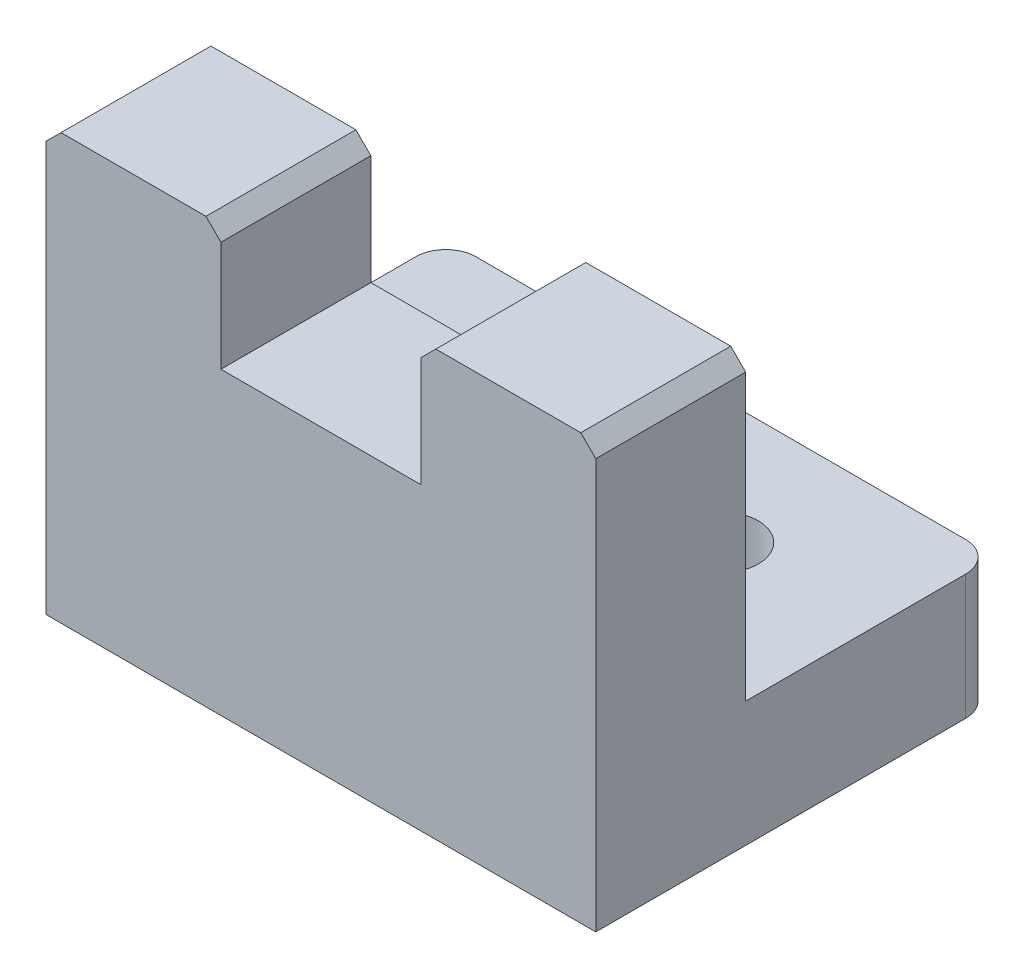
SolidWorks part; units mm, degrees
ref_plane "Front Plane" through (0, 0, 0) normal (0, 0, 1) x (1, 0, 0)
ref_plane "Top Plane" through (0, 0, 0) normal (0, 1, 0) x (1, 0, 0)
ref_plane "Right Plane" through (0, 0, 0) normal (1, 0, 0) x (0, 0, -1)
sketch "Sketch1" plane through (0, 0, 0) normal (0, 1, 0) x (1, 0, 0)
  line L1 (-55, 40) -> (55, 40)
  line L2 (-55, 40) -> (-55, -40)
  line L3 (-55, -40) -> (55, -40)
  line L4 (55, 40) -> (55, -40)
  dimension "D1" = 110
  dimension "D2" = 80
  dimension "D3" = 40
  dimension "D4" = 55
extrude "Boss-Extrude1" add sketch "Sketch1" along normal mid plane 25
sketch "Sketch2" plane through (0, 12.5, 0) normal (0, 1, 0) x (1, 0, 0)
  line L0 (55, -40) -> (55, 40) construction
  line L1 (-55, -40) -> (55, -40)
  line L2 (-55, -40) -> (-55, -10)
  line L3 (-55, -10) -> (55, -10)
  line L4 (55, -40) -> (55, -10)
  dimension "D1" = 30
extrude "Boss-Extrude2" add sketch "Sketch2" along normal blind 60
sketch "Sketch3" plane through (0, 0, 10) normal (0, 0, -1) x (-1, 0, 0)
  line L0 (-55, 72.5) -> (55, 72.5) construction
  line L1 (-20, 72.5) -> (20, 72.5)
  line L2 (-20, 72.5) -> (-20, 47.5)
  line L3 (-20, 47.5) -> (20, 47.5)
  line L4 (20, 72.5) -> (20, 47.5)
  line L5 (-55, 72.5) -> (-55, 12.5) construction
  dimension "D1" = 40
  dimension "D2" = 35
  dimension "D3" = 25
extrude "Cut-Extrude1" cut sketch "Sketch3" against normal through all
chamfer "Chamfer1" distance 3 distance2 3 4 edges at (55, 72.5, 25) (20, 72.5, 25) (-55, 72.5, 25) (-20, 72.5, 25)
fillet "Fillet1" radius 6 2 edges at (-55, 0, -40) (55, 0, -40)
hole_wizard "Ø1.0mm Dowel Hole1" positions "Sketch4" profile "Sketch5" hole size "Ø1.0" standard "ISO" end condition through all
sketch "Sketch4" plane through (0, 12.5, 0) normal (0, 1, 0) x (1, 0, 0)
  line L0 (55, -10) -> (55, 34) construction
  line L1 (55, -10) -> (-55, -10) construction
  point P0 (25, 15)
  point P2 (-25, 15)
  dimension "D1" = 50
  dimension "D2" = 30
  dimension "D3" = 25
sketch "Sketch5" plane through (25, 12.5, -15) normal (1, 0, 0) x (0, 0, 1)
  line L0 (0, 0) -> (0, 25)
  line L1 (0, 25) -> (7.5, 25)
  line L2 (7.5, 25) -> (7.5, 0)
  line L5 (7.5, 0) -> (0, 0)
  line L11 (0, -6.35) -> (0, 107.95) construction
  dimension "Thru Hole Dia." = 15
  dimension "Thru Hole Depth" = 25
